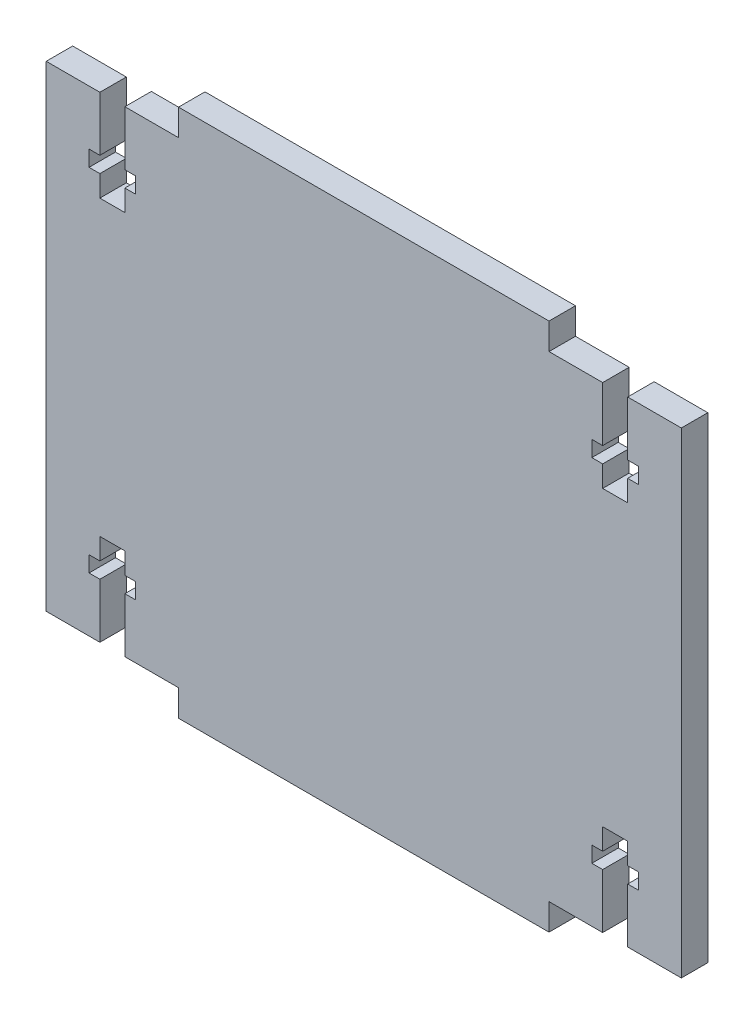
SolidWorks part; units mm, degrees
ref_plane "Front Plane" through (0, 0, 0) normal (0, 0, 1) x (1, 0, 0)
ref_plane "Top Plane" through (0, 0, 0) normal (0, 1, 0) x (1, 0, 0)
ref_plane "Right Plane" through (0, 0, 0) normal (1, 0, 0) x (0, 0, -1)
sketch "Sketch1" plane through (0, 0, 0) normal (0, 0, 1) x (1, 0, 0)
  line L1 (-38.1, -31.75) -> (38.1, -31.75)
  line L2 (-38.1, -31.75) -> (-38.1, 31.75)
  line L3 (-38.1, 31.75) -> (38.1, 31.75)
  line L4 (38.1, -31.75) -> (38.1, 31.75)
  line L5 (-38.1, -31.75) -> (38.1, 31.75) construction
  line L6 (-38.1, 31.75) -> (38.1, -31.75) construction
  point P0 (0, 0)
  dimension "D1" = 76.2
  dimension "D2" = 63.5
extrude "Boss-Extrude1" add sketch "Sketch1" along normal blind 3.175
sketch "Sketch2" plane through (0, 0, 0) normal (0, 0, -1) x (-1, 0, 0)
  line L0 (-38.1, 0) -> (38.1, 0) construction
  line L1 (-38.1, -31.75) -> (-22.225, -31.75)
  line L2 (-38.1, -31.75) -> (-38.1, -28.575)
  line L3 (-38.1, -28.575) -> (-22.225, -28.575)
  line L4 (-22.225, -31.75) -> (-22.225, -28.575)
  line L5 (38.1, -31.75) -> (22.225, -31.75)
  line L6 (38.1, -31.75) -> (38.1, -28.575)
  line L7 (38.1, -28.575) -> (22.225, -28.575)
  line L8 (22.225, -31.75) -> (22.225, -28.575)
  line L9 (-38.1, -31.75) -> (-38.1, 31.75) construction
  line L10 (38.1, 31.75) -> (38.1, -31.75) construction
  line L11 (22.225, 31.75) -> (22.225, 28.575)
  line L12 (38.1, 28.575) -> (22.225, 28.575)
  line L13 (38.1, 31.75) -> (38.1, 28.575)
  line L14 (38.1, 31.75) -> (22.225, 31.75)
  line L15 (-22.225, 31.75) -> (-22.225, 28.575)
  line L16 (-38.1, 28.575) -> (-22.225, 28.575)
  line L17 (-38.1, 31.75) -> (-38.1, 28.575)
  line L18 (-38.1, 31.75) -> (-22.225, 31.75)
  dimension "D1" = 3.175
  dimension "D2" = 44.45
extrude "Cut-Extrude1" cut sketch "Sketch2" against normal through all
sketch "Sketch3" plane through (0, 0, 3.175) normal (0, 0, 1) x (1, 0, 0)
  line L0 (31.6625, -17.575) -> (31.6625, -20.125)
  line L1 (31.6625, -17.575) -> (28.6625, -17.575)
  line L2 (31.6625, -28.575) -> (28.6625, -28.575)
  line L3 (28.6625, -17.575) -> (28.6625, -20.125)
  line L4 (31.6625, -17.575) -> (28.6625, -28.575) construction
  line L5 (31.6625, -28.575) -> (28.6625, -17.575) construction
  line L6 (28.6625, -22.025) -> (28.6625, -28.575)
  line L7 (27.3625, -22.025) -> (27.3625, -20.125)
  line L8 (27.3625, -22.025) -> (28.6625, -22.025)
  line L9 (32.9625, -22.025) -> (32.9625, -20.125)
  line L10 (27.3625, -20.125) -> (28.6625, -20.125)
  line L11 (27.3625, -22.025) -> (32.9625, -20.125) construction
  line L12 (32.9625, -22.025) -> (27.3625, -20.125) construction
  line L13 (31.6625, -22.025) -> (31.6625, -28.575)
  line L14 (28.6625, -20.125) -> (28.6625, -22.025) construction
  line L15 (31.6625, -17.575) -> (31.6625, -22.025) construction
  line L16 (31.6625, -22.025) -> (32.9625, -22.025)
  line L17 (31.6625, -20.125) -> (32.9625, -20.125)
  line L18 (28.6625, -20.125) -> (31.6625, -20.125) construction
  line L19 (31.6625, -22.025) -> (28.6625, -22.025) construction
  line L20 (22.225, -28.575) -> (38.1, -28.575) construction
  line L21 (0, 31.75) -> (0, -31.75) construction
  line L22 (22.225, 31.75) -> (-22.225, 31.75) construction
  line L23 (-22.225, -31.75) -> (22.225, -31.75) construction
  line L24 (-31.6625, -22.025) -> (-28.6625, -22.025) construction
  line L25 (-28.6625, -20.125) -> (-31.6625, -20.125) construction
  line L26 (-31.6625, -17.575) -> (-31.6625, -22.025) construction
  line L27 (-28.6625, -20.125) -> (-28.6625, -22.025) construction
  line L28 (-32.9625, -22.025) -> (-27.3625, -20.125) construction
  line L29 (-27.3625, -22.025) -> (-32.9625, -20.125) construction
  line L30 (-31.6625, -28.575) -> (-28.6625, -17.575) construction
  line L31 (-31.6625, -17.575) -> (-28.6625, -28.575) construction
  line L32 (-31.6625, -20.125) -> (-32.9625, -20.125)
  line L33 (-31.6625, -22.025) -> (-32.9625, -22.025)
  line L34 (-31.6625, -22.025) -> (-31.6625, -28.575)
  line L35 (-27.3625, -20.125) -> (-28.6625, -20.125)
  line L36 (-32.9625, -22.025) -> (-32.9625, -20.125)
  line L37 (-27.3625, -22.025) -> (-28.6625, -22.025)
  line L38 (-27.3625, -22.025) -> (-27.3625, -20.125)
  line L39 (-28.6625, -22.025) -> (-28.6625, -28.575)
  line L40 (-28.6625, -17.575) -> (-28.6625, -20.125)
  line L41 (-31.6625, -28.575) -> (-28.6625, -28.575)
  line L42 (-31.6625, -17.575) -> (-28.6625, -17.575)
  line L43 (-31.6625, -17.575) -> (-31.6625, -20.125)
  line L44 (-38.1, 0) -> (38.1, 0) construction
  line L45 (-38.1, 28.575) -> (-38.1, -28.575) construction
  line L46 (38.1, -28.575) -> (38.1, 28.575) construction
  line L47 (31.6625, 22.025) -> (28.6625, 22.025) construction
  line L48 (28.6625, 20.125) -> (31.6625, 20.125) construction
  line L49 (31.6625, 17.575) -> (31.6625, 22.025) construction
  line L50 (28.6625, 20.125) -> (28.6625, 22.025) construction
  line L51 (32.9625, 22.025) -> (27.3625, 20.125) construction
  line L52 (27.3625, 22.025) -> (32.9625, 20.125) construction
  line L53 (31.6625, 28.575) -> (28.6625, 17.575) construction
  line L54 (31.6625, 17.575) -> (28.6625, 28.575) construction
  line L55 (31.6625, 20.125) -> (32.9625, 20.125)
  line L56 (31.6625, 22.025) -> (32.9625, 22.025)
  line L57 (31.6625, 22.025) -> (31.6625, 28.575)
  line L58 (27.3625, 20.125) -> (28.6625, 20.125)
  line L59 (32.9625, 22.025) -> (32.9625, 20.125)
  line L60 (27.3625, 22.025) -> (28.6625, 22.025)
  line L61 (27.3625, 22.025) -> (27.3625, 20.125)
  line L62 (28.6625, 22.025) -> (28.6625, 28.575)
  line L63 (28.6625, 17.575) -> (28.6625, 20.125)
  line L64 (31.6625, 28.575) -> (28.6625, 28.575)
  line L65 (31.6625, 17.575) -> (28.6625, 17.575)
  line L66 (31.6625, 17.575) -> (31.6625, 20.125)
  line L67 (-31.6625, 17.575) -> (-28.6625, 28.575) construction
  line L68 (-31.6625, 28.575) -> (-28.6625, 17.575) construction
  line L69 (-27.3625, 22.025) -> (-32.9625, 20.125) construction
  line L70 (-32.9625, 22.025) -> (-27.3625, 20.125) construction
  line L71 (-28.6625, 20.125) -> (-28.6625, 22.025) construction
  line L72 (-31.6625, 17.575) -> (-31.6625, 22.025) construction
  line L73 (-28.6625, 20.125) -> (-31.6625, 20.125) construction
  line L74 (-31.6625, 22.025) -> (-28.6625, 22.025) construction
  line L75 (-31.6625, 17.575) -> (-31.6625, 20.125)
  line L76 (-31.6625, 17.575) -> (-28.6625, 17.575)
  line L77 (-31.6625, 28.575) -> (-28.6625, 28.575)
  line L78 (-28.6625, 17.575) -> (-28.6625, 20.125)
  line L79 (-28.6625, 22.025) -> (-28.6625, 28.575)
  line L80 (-27.3625, 22.025) -> (-27.3625, 20.125)
  line L81 (-27.3625, 22.025) -> (-28.6625, 22.025)
  line L82 (-32.9625, 22.025) -> (-32.9625, 20.125)
  line L83 (-27.3625, 20.125) -> (-28.6625, 20.125)
  line L84 (-31.6625, 22.025) -> (-31.6625, 28.575)
  line L85 (-31.6625, 22.025) -> (-32.9625, 22.025)
  line L86 (-31.6625, 20.125) -> (-32.9625, 20.125)
  point P0 (30.1625, -28.575)
  point P5 (30.1625, -21.075)
  point P35 (-30.1625, -21.075)
  point P36 (-30.1625, -28.575)
  point P55 (30.1625, 21.075)
  point P56 (30.1625, 28.575)
  point P69 (-30.1625, 28.575)
  point P70 (-30.1625, 21.075)
  dimension "D1" = 11
  dimension "D2" = 5.6
  dimension "D3" = 1.9
  dimension "D4" = 3.5
  dimension "D5" = 3
extrude "Cut-Extrude2" cut sketch "Sketch3" against normal through all
